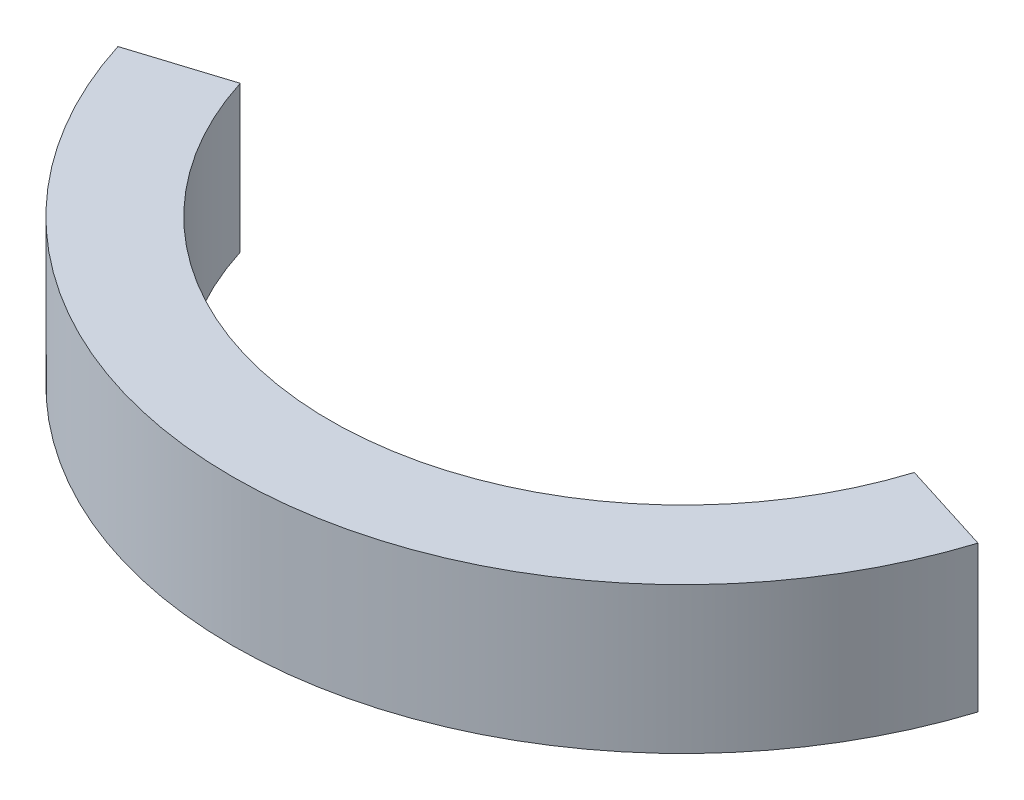
SolidWorks part; units mm, degrees
ref_plane "Front" through (0, 0, 0) normal (0, 0, 1) x (1, 0, 0)
ref_plane "Top" through (0, 0, 0) normal (0, 1, 0) x (1, 0, 0)
ref_plane "Right" through (0, 0, 0) normal (1, 0, 0) x (0, 0, -1)
sketch "Sketch1" plane through (0, 0, 0) normal (0, 1, 0) x (1, 0, 0)
  line L0 (-112.0379, -35.3254) -> (-87.8135, -27.6875)
  line L1 (87.8135, -27.6875) -> (112.0379, -35.3254)
  line L2 (-87.8135, -27.6875) -> (0, 0) construction
  line L3 (0, 0) -> (87.8135, -27.6875) construction
  line L4 (0, 0) -> (0, -117.475) construction
  line L5 (-87.8135, -27.6875) -> (0, -117.475) construction
  line L6 (0, -117.475) -> (87.8135, -27.6875) construction
  arc A0 (-112.0379, -35.3254) -> (112.0379, -35.3254) centre (0, 0) ccw
  arc A1 (-87.8135, -27.6875) -> (87.8135, -27.6875) centre (0, 0) ccw
  dimension "D1" = 25.4
  dimension "D2" = 117.475
  dimension "D3" = 145
extrude "Boss-Extrude1" add sketch "Sketch1" against normal blind 38.1
